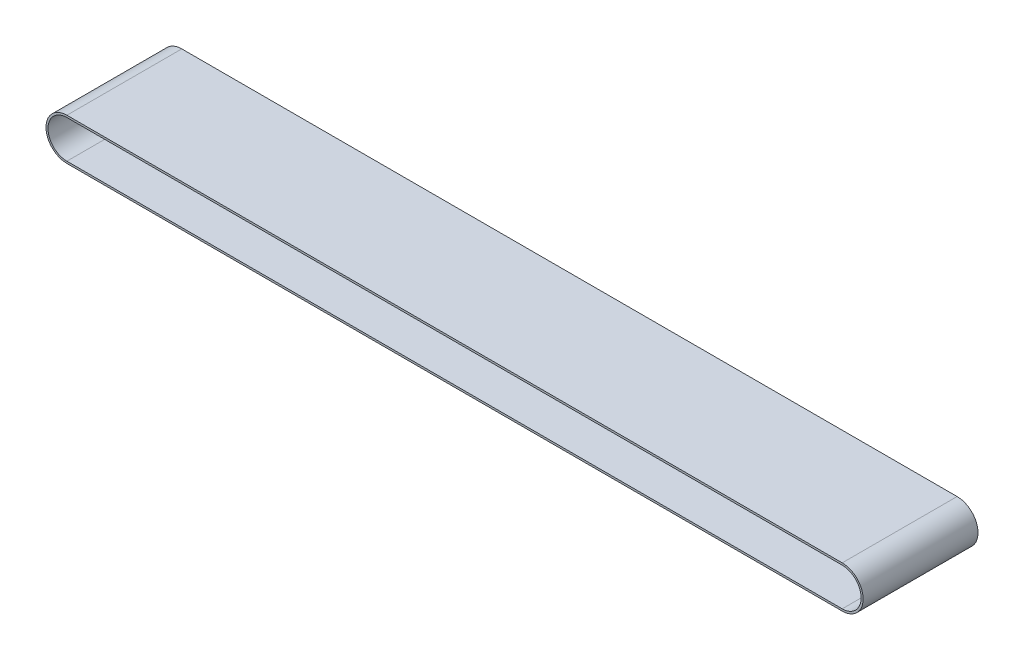
SolidWorks part; units mm, degrees
ref_plane "Front Plane" through (0, 0, 0) normal (0, 0, 1) x (1, 0, 0)
ref_plane "Top Plane" through (0, 0, 0) normal (0, 1, 0) x (1, 0, 0)
ref_plane "Right Plane" through (0, 0, 0) normal (1, 0, 0) x (0, 0, -1)
sketch "Sketch1" plane through (0, 0, 0) normal (0, 0, 1) x (1, 0, 0)
  line L0 (0, 35.8) -> (664.2, 35.8)
  line L1 (0, 0) -> (664.2, 0)
  arc A0 (0, 0) -> (0, 35.8) centre (0, 17.9) cw
  arc A1 (664.2, 35.8) -> (664.2, 0) centre (664.2, 17.9) cw
  dimension "D1" = 664.2
  dimension "D2" = 35.8
extrude "Boss-Extrude1" add sketch "Sketch1" along normal blind 98.425 contours L0 A1 L1 A0
sketch "Sketch3" plane through (0, 0, 98.425) normal (0, 0, 1) x (1, 0, 0)
  line L0 (0, 34.1) -> (664.2, 34.1)
  line L1 (0, 1.7) -> (664.2, 1.7)
  line L4 (0, 35.8) -> (664.2, 35.8) construction
  line L5 (0, 0) -> (664.2, 0) construction
  arc A0 (0, 34.1) -> (0, 1.7) centre (0, 17.9) ccw
  arc A1 (664.2, 34.1) -> (664.2, 1.7) centre (664.2, 17.9) cw
  dimension "D4" = 664.2
  dimension "D5" = 16.2
  dimension "D6" = 16.2
  dimension "D1" = 1.7
  dimension "D2" = 1.7
  dimension "D3" = 664.2
extrude "Cut-Extrude1" cut sketch "Sketch3" against normal up to next contours L0 A1 L1 A0
